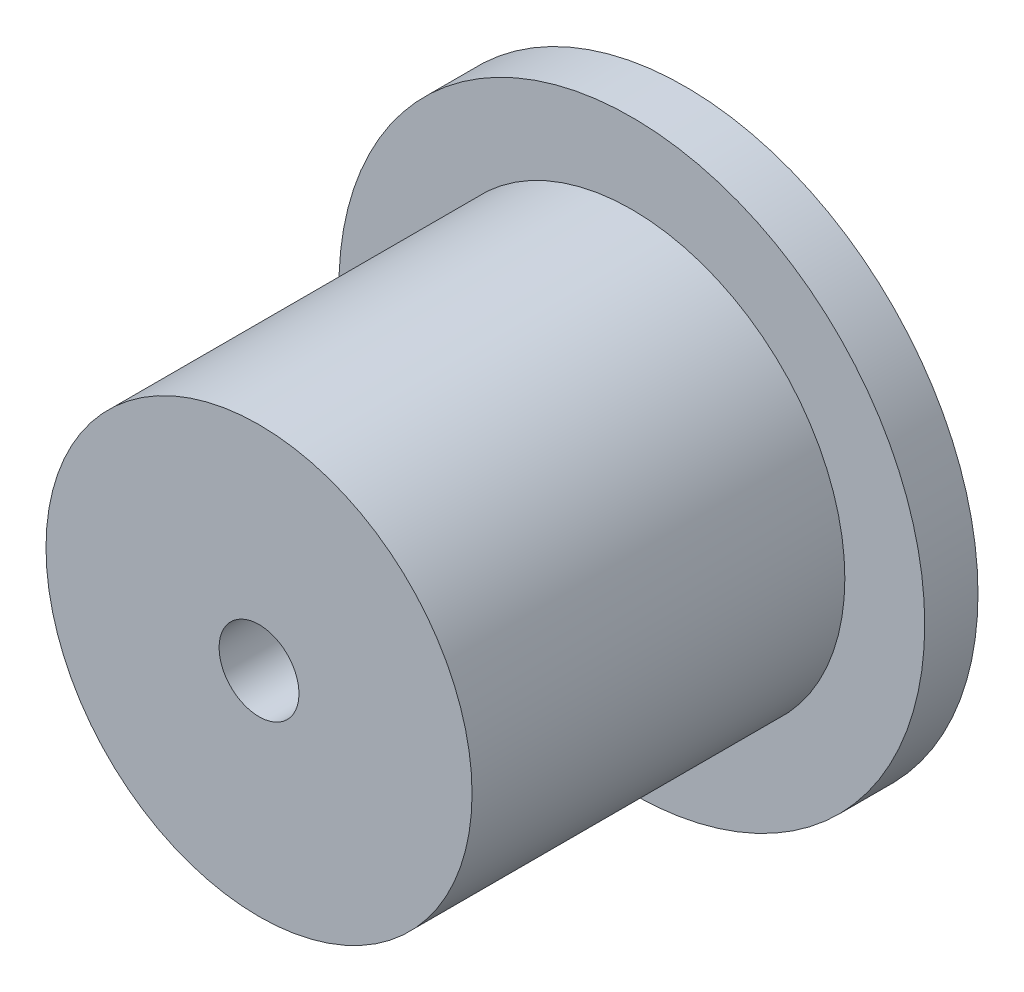
SolidWorks part; units mm, degrees
material "AISI 316 Annealed Stainless Steel Bar (SS)"
ref_plane "Front Plane" through (0, 0, 0) normal (0, 0, 1) x (1, 0, 0)
ref_plane "Top Plane" through (0, 0, 0) normal (0, 1, 0) x (1, 0, 0)
ref_plane "Right Plane" through (0, 0, 0) normal (1, 0, 0) x (0, 0, -1)
sketch "Sketch1" plane through (0, 0, 0) normal (0, 0, 1) x (1, 0, 0)
  circle A0 centre (0, 0) radius 11
  dimension "D1" = 22
extrude "Boss-Extrude1" add sketch "Sketch1" along normal blind 2
sketch "Sketch2" plane through (0, 0, 2) normal (0, 0, 1) x (1, 0, 0)
  circle A0 centre (0, 0) radius 8
  dimension "D1" = 16
extrude "Boss-Extrude2" add sketch "Sketch2" along normal blind 14
hole_wizard "CBORE for M5 Hex Head Bolt1" positions "Sketch3" profile "Sketch4" counterbore size "M5" standard "ANSI Metric" end condition through all
sketch "Sketch3" plane through (0, 0, 0) normal (0, 0, -1) x (-1, 0, 0)
  point P0 (0, 0)
sketch "Sketch4" plane through (0, 0, 0) normal (1, 0, 0) x (0, 1, 0)
  line L0 (0, 0) -> (0, 16)
  line L1 (0, 16) -> (1.5, 16)
  line L3 (1.5, 16) -> (1.5, 3)
  line L4 (1.5, 3) -> (3, 3)
  line L5 (3, 3) -> (3, 0)
  line L7 (3, 0) -> (0, 0)
  line L11 (0, -6.35) -> (0, 107.95) construction
  dimension "Thru Hole Dia." = 3
  dimension "Thru Hole Depth" = 16
  dimension "C'Bore Dia." = 6
  dimension "C'Bore Depth" = 3
